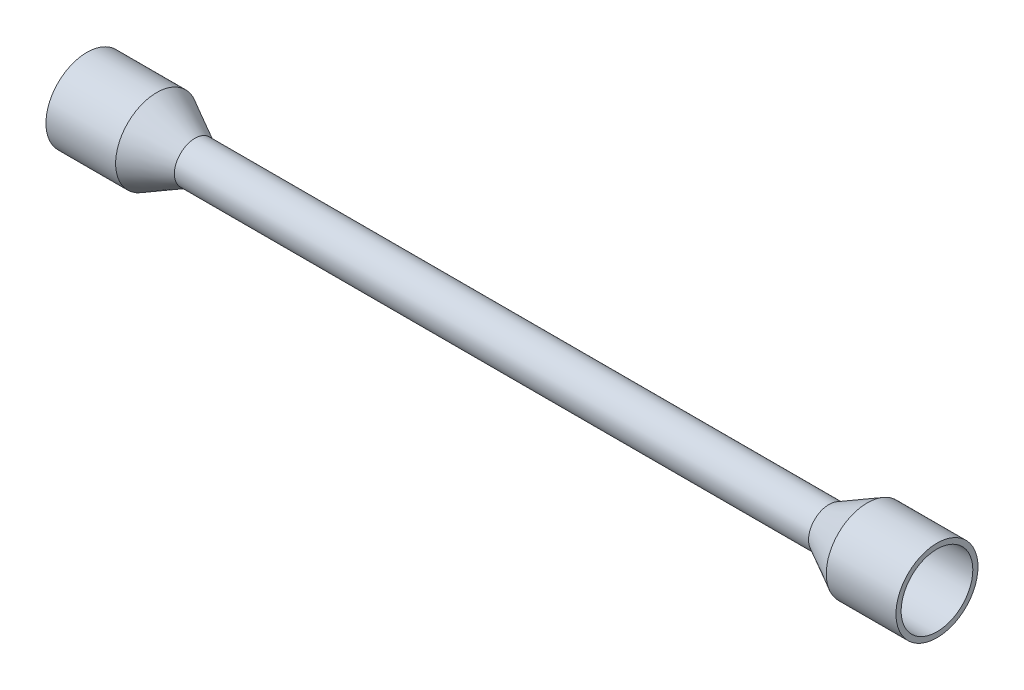
SolidWorks part; units mm, degrees
ref_plane "Plano frontal" through (0, 0, 0) normal (0, 0, 1) x (1, 0, 0)
ref_plane "Plano superior" through (0, 0, 0) normal (0, 1, 0) x (1, 0, 0)
ref_plane "Plano direito" through (0, 0, 0) normal (1, 0, 0) x (0, 0, -1)
sketch "Sketch1" plane through (0, 0, 0) normal (0, 1, 0) x (1, 0, 0)
  line L0 (250, 0) -> (-250, 0) construction
  line L1 (-250, 0) -> (-250, 24.125) construction
  line L2 (-250, 24.125) -> (-209, 24.125)
  line L3 (-186.4955, 12.0625) -> (0, 12.0625)
  line L4 (-209, 24.125) -> (-186.4955, 12.0625)
  line L5 (-250, 21.075) -> (-209.7659, 21.075)
  line L6 (-209.7659, 21.075) -> (-187.2614, 9.0125)
  line L7 (-187.2614, 9.0125) -> (-187.2614, 0)
  line L8 (-187.2614, 9.0125) -> (0, 9.0125) construction
  line L9 (0, 0) -> (0, -61.9409) construction
  line L10 (250, 0) -> (250, 24.125) construction
  line L11 (187.2614, 9.0125) -> (187.2614, 0)
  line L12 (209.7659, 21.075) -> (187.2614, 9.0125)
  line L13 (250, 21.075) -> (209.7659, 21.075)
  line L14 (209, 24.125) -> (186.4955, 12.0625)
  line L15 (186.4955, 12.0625) -> (0, 12.0625)
  line L16 (250, 24.125) -> (209, 24.125)
  line L17 (-250, 21.075) -> (-250, 24.125)
  line L18 (250, 24.125) -> (250, 21.075)
  line L19 (187.2614, 0) -> (-187.2614, 0)
  dimension "D1" = 3.05
revolve "Revolve1" add sketch "Sketch1" angle 360 about L0
